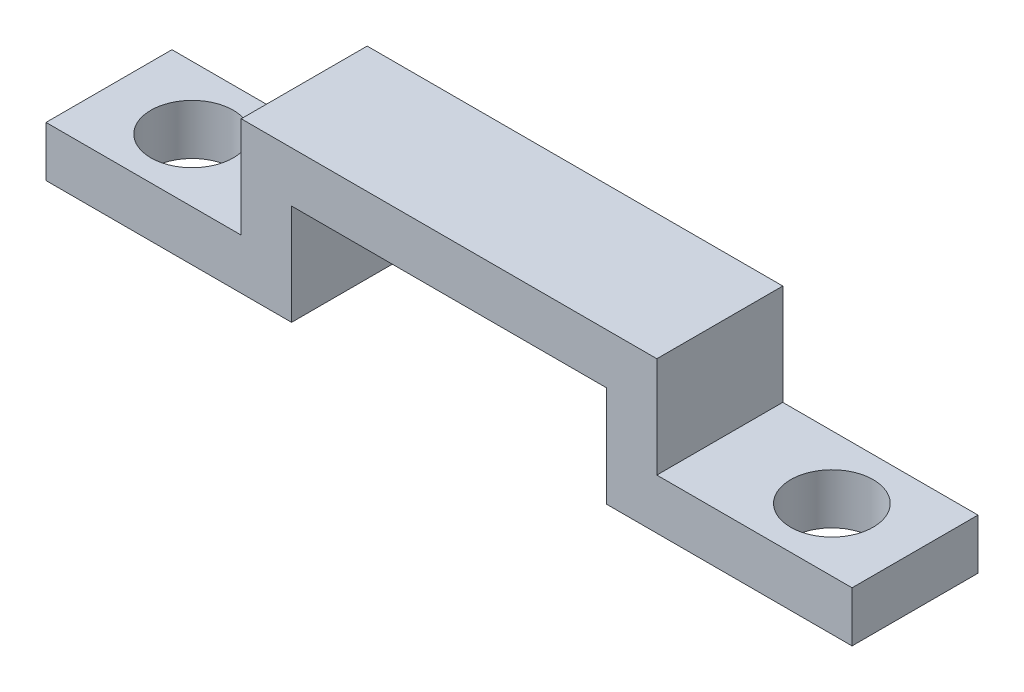
SolidWorks part; units mm, degrees
ref_plane "Front" through (0, 0, 0) normal (0, 0, 1) x (1, 0, 0)
ref_plane "Top" through (0, 0, 0) normal (0, 1, 0) x (1, 0, 0)
ref_plane "Right" through (0, 0, 0) normal (1, 0, 0) x (0, 0, -1)
sketch "Sketch1" plane through (0, 0, 0) normal (0, 0, 1) x (1, 0, 0)
  line L0 (0, 0) -> (0, 31.6793) construction
  line L1 (-16, 0) -> (-6.25, 0)
  line L2 (-6.25, 0) -> (-6.25, 4)
  line L3 (-6.25, 4) -> (0, 4)
  line L4 (-16, 2) -> (-8.25, 2)
  line L5 (-8.25, 2) -> (-8.25, 6)
  line L6 (-8.25, 6) -> (0, 6)
  line L7 (-16, 2) -> (-16, 0)
  line L8 (16, 2) -> (16, 0)
  line L9 (8.25, 6) -> (0, 6)
  line L10 (8.25, 2) -> (8.25, 6)
  line L11 (16, 2) -> (8.25, 2)
  line L12 (6.25, 4) -> (0, 4)
  line L13 (6.25, 0) -> (6.25, 4)
  line L14 (16, 0) -> (6.25, 0)
  dimension "D2" = 12.5
  dimension "D3" = 4
  dimension "D4" = 32
  dimension "D1" = 2
extrude "Boss-Extrude1" add sketch "Sketch1" along normal blind 5
sketch "Sketch2" plane through (0, 2, 0) normal (0, 1, 0) x (1, 0, 0)
  line L0 (-12.7, -2.5) -> (12.7, -2.5) construction
  line L1 (-12.7, -2.5) -> (-16, -2.5) construction
  line L2 (-16, -5) -> (-16, 0) construction
  line L3 (0, 0) -> (0, -5) construction
  line L4 (8.25, -5) -> (-8.25, -5) construction
  circle A0 centre (-12.7, -2.5) radius 1.6383
  circle A1 centre (12.7, -2.5) radius 1.6383
  point P12 (0, -2.5)
  dimension "D1" = 3.2766
  dimension "D2" = 25.4
extrude "Cut-Extrude1" cut sketch "Sketch2" against normal blind 5
